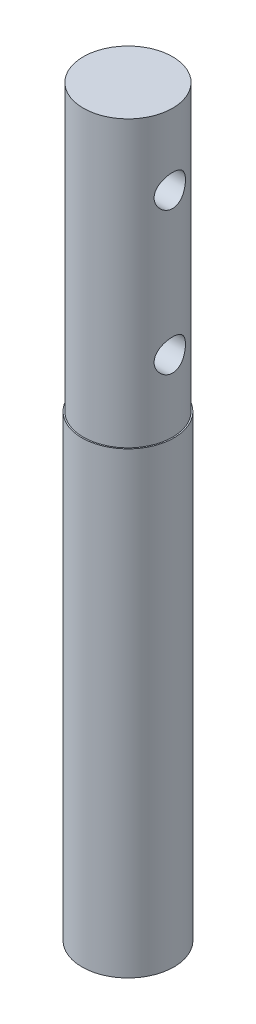
SolidWorks part; units mm, degrees
material "ASTM A36 Steel"
ref_plane "Front Plane" through (0, 0, 0) normal (0, 0, 1) x (1, 0, 0)
ref_plane "Top Plane" through (0, 0, 0) normal (0, 1, 0) x (1, 0, 0)
ref_plane "Right Plane" through (0, 0, 0) normal (1, 0, 0) x (0, 0, -1)
sketch "Sketch1" plane through (0, 0, 0) normal (0, 1, 0) x (1, 0, 0)
  circle A0 centre (0, 0) radius 32.25
  dimension "D1" = 64.5
extrude "Boss-Extrude1" add sketch "Sketch1" along normal blind 321.7
sketch "Sketch2" plane through (0, 321.7, 0) normal (0, 1, 0) x (1, 0, 0)
  circle A0 centre (0, 0) radius 31.34
  dimension "D1" = 62.68
extrude "Boss-Extrude2" add sketch "Sketch2" along normal blind 200
ref_plane "Plane1" through (25, 0, 0) normal (1, 0, 0) x (0, 0, -1)
sketch "Sketch3" plane through (0, 0, 0) normal (1, 0, 0) x (0, 0, -1)
  line L2 (31.34, 521.7) -> (-31.34, 521.7) construction
  circle A0 centre (0, 471.7) radius 11
  circle A1 centre (0, 371.7) radius 11
  dimension "D1" = 22
  dimension "D2" = 50
  dimension "D3" = 22
  dimension "D4" = 100
extrude "Cut-Extrude1" cut sketch "Sketch3" against normal through all both and the other way through all
